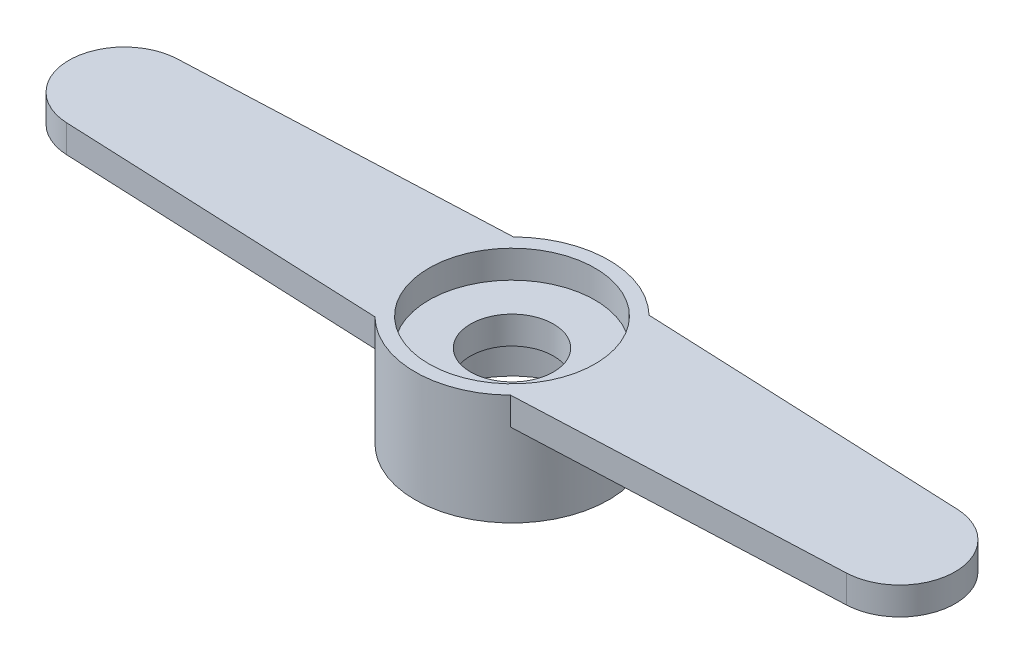
SolidWorks part; units mm, degrees
ref_plane "前视基准面" through (0, 0, 0) normal (0, 0, 1) x (1, 0, 0)
ref_plane "上视基准面" through (0, 0, 0) normal (0, 1, 0) x (1, 0, 0)
ref_plane "右视基准面" through (0, 0, 0) normal (1, 0, 0) x (0, 0, -1)
sketch "草图1" plane through (0, 0, 0) normal (0, 1, 0) x (1, 0, 0)
  circle A0 centre (0, 0) radius 1.5
  circle A1 centre (0, 0) radius 3.5
  dimension "D1" = 3
  dimension "D2" = 7
extrude "凸台-拉伸1" add sketch "草图1" along normal blind 4
sketch "草图2" plane through (0, 0, 0) normal (0, -1, 0) x (1, 0, 0)
  circle A0 centre (0, 0) radius 3
  dimension "D1" = 6
extrude "切除-拉伸1" cut sketch "草图2" against normal blind 2
sketch "草图3" plane through (0, 4, 0) normal (0, 1, 0) x (1, 0, 0)
  circle A0 centre (0, 0) radius 3
extrude "切除-拉伸2" cut sketch "草图3" against normal blind 1
sketch "草图4" plane through (0, 4, 0) normal (0, 1, 0) x (1, 0, 0)
  line L0 (-16.2027, 0) -> (17.9417, 0) construction
  line L1 (0, 8.1121) -> (0, -7.6086) construction
  line L2 (-6.4391, 2.5) -> (-6.4391, -2.5) construction
  line L3 (-6.4391, 2.5) -> (4.5072, 2.5) construction
  line L4 (14.0862, 1.9981) -> (2.4495, 2.5)
  line L5 (-14.0862, 1.9981) -> (-2.4495, 2.5)
  line L6 (14.0862, -1.9981) -> (2.4495, -2.5)
  line L7 (-14.0862, -1.9981) -> (-2.4495, -2.5)
  circle A0 centre (-14, 0) radius 2
  circle A1 centre (14, 0) radius 2
  circle A3 centre (0, 0) radius 3.5 construction
  arc A4 (-2.4495, -2.5) -> (-2.4495, 2.5) centre (0.0505, 0) cw
  arc A5 (2.4495, 2.5) -> (2.4495, -2.5) centre (0, 0) cw
  circle M10 centre (0, 0) radius 3.5
  dimension "D1" = 14
  dimension "D2" = 4
  dimension "D3" = 2.5
  dimension "D4" = 2.5
extrude "凸台-拉伸2" add sketch "草图4" against normal blind 1 contours A0 L7 L5 M10 | L6 A1 L4 M10 | A0 | A1
